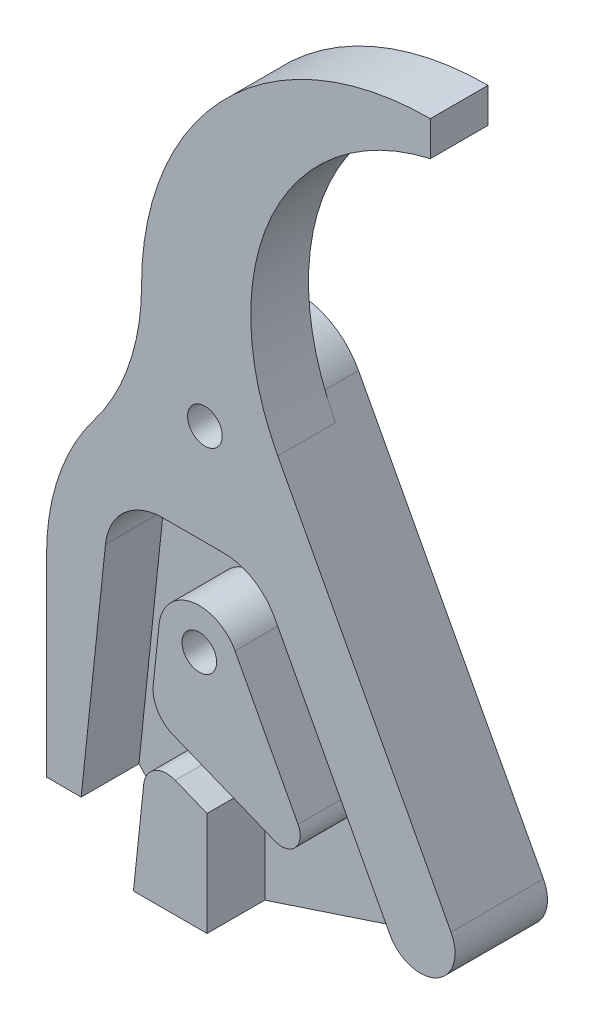
SolidWorks part; units mm, degrees
ref_plane "Alzado" through (0, 0, 0) normal (0, 0, 1) x (1, 0, 0)
ref_plane "Planta" through (0, 0, 0) normal (0, 1, 0) x (1, 0, 0)
ref_plane "Vista lateral" through (0, 0, 0) normal (1, 0, 0) x (0, 0, -1)
sketch "Croquis1" plane through (0, 0, 0) normal (0, 0, 1) x (1, 0, 0)
  line L0 (0, 0) -> (3.2081, 30.5226)
  line L1 (8.1807, 35) -> (13.4351, 35)
  line L2 (17.8498, 32.3474) -> (74.7762, -74.7155)
  line L3 (-45.5316, -5.3258) -> (-45.5316, 25.382)
  line L4 (0, 0) -> (0, 124.083) construction
  line L5 (14.4224, 28.1432) -> (19.8837, 17.8719)
  line L6 (7.8513, 26.8658) -> (7.3413, 22.014)
  line L7 (17.8498, 32.3474) -> (5.7848, 55.0384) construction
  line L8 (5.7848, 55.0384) -> (3.2081, 30.5226) construction
  line L9 (17.8538, 15.6175) -> (9.0466, 19.1759)
  line L10 (25.2121, 15.5) -> (11.8352, 15.5) construction
  line L11 (12.9137, 30) -> (5.536, 30) construction
  line L12 (6.4174, 22.7498) -> (9.4633, 17.0212) construction
  line L13 (5.0275, 0) -> (6.521, 14.2091)
  line L14 (9.2592, 15.8544) -> (17.7727, 12.4147)
  line L15 (6.3558, 16) -> (10.5824, 16) construction
  arc A0 (14.4224, 28.1432) -> (7.8513, 26.8658) centre (11.3321, 26.5) ccw
  arc A1 (17.8498, 32.3474) -> (13.4351, 35) centre (13.4351, 30) ccw
  arc A2 (8.1807, 35) -> (3.2081, 30.5226) centre (8.1807, 30) ccw
  arc A3 (7.3413, 22.014) -> (9.0466, 19.1759) centre (10.0771, 21.7264) ccw
  arc A4 (19.8837, 17.8719) -> (17.8538, 15.6175) centre (18.4585, 17.1142) cw
  arc A5 (6.521, 14.2091) -> (9.2592, 15.8544) centre (8.51, 14) cw
  dimension "D2" = 3.5
  dimension "D3" = 5
  dimension "D6" = 5
  dimension "D9" = 35
  dimension "D8" = 5
  dimension "D16" = 2
  dimension "D1" = 34
  dimension "D4" = 6
  dimension "D5" = 5
  dimension "D7" = 8.5
  dimension "D10" = 106
  dimension "D11" = 14.5
  dimension "D12" = 9.6
  dimension "D13" = 3
  dimension "D14" = 16
  dimension "D15" = 5
sketch "Croquis4" plane through (0, 0, 0) normal (0, 0, 1) x (1, 0, 0)
  line L0 (8.1807, 35) -> (13.4351, 35) construction
  line L1 (31.3321, 76.5) -> (69.3272, 76.5) construction
  line L2 (31.3321, 76.5) -> (31.3321, 73.5)
  line L3 (17.8538, 15.6175) -> (9.0466, 19.1759) construction
  line L5 (8.1807, 35) -> (13.4351, 35)
  line L6 (7.8513, 26.8658) -> (7.3413, 22.014)
  line L7 (7.8513, 26.8658) -> (7.3413, 22.014) construction
  line L8 (3.2081, 30.5226) -> (1.106, 10.5226)
  line L9 (0, 0) -> (3.2081, 30.5226) construction
  line L10 (17.8498, 32.3474) -> (27.8225, 13.5916)
  line L11 (17.8498, 32.3474) -> (74.7762, -74.7155) construction
  line L12 (6.521, 14.2091) -> (5.6316, 5.747)
  line L13 (14.4224, 28.1432) -> (19.8837, 17.8719) construction
  line L14 (17.8538, 15.6175) -> (9.0466, 19.1759)
  line L15 (1.106, 10.5226) -> (-1.894, 10.5226)
  line L16 (-1.894, 10.5226) -> (-1.894, 27.2014)
  line L17 (14.4224, 28.1432) -> (19.8837, 17.8719)
  line L18 (33.1201, 16.4084) -> (18.124, 44.6121)
  line L19 (5.0275, 0) -> (6.521, 14.2091) construction
  line L20 (9.2592, 15.8544) -> (12, 14.747)
  line L21 (9.2592, 15.8544) -> (17.7727, 12.4147) construction
  line L22 (12, 14.747) -> (12, 5.747)
  line L23 (12, 5.747) -> (5.6316, 5.747)
  line L25 (0, 0) -> (0, 124.083) construction
  line L26 (6.3321, 51.5) -> (-1.894, 27.2014) construction
  line L27 (17.8498, 32.3474) -> (5.7848, 55.0384) construction
  arc A0 (17.8498, 32.3474) -> (13.4351, 35) centre (13.4351, 30) ccw construction
  arc A1 (8.1807, 35) -> (3.2081, 30.5226) centre (8.1807, 30) ccw construction
  arc A2 (14.4224, 28.1432) -> (7.8513, 26.8658) centre (11.3321, 26.5) ccw construction
  arc A3 (17.8498, 32.3474) -> (13.4351, 35) centre (13.4351, 30) ccw
  arc A4 (8.1807, 35) -> (3.2081, 30.5226) centre (8.1807, 30) ccw
  arc A5 (14.4224, 28.1432) -> (7.8513, 26.8658) centre (11.3321, 26.5) ccw
  circle A6 centre (11.3321, 26.5) radius 1.5
  arc A7 (27.8225, 13.5916) -> (33.1201, 16.4084) centre (30.4713, 15) ccw
  arc A8 (7.3413, 22.014) -> (9.0466, 19.1759) centre (10.0771, 21.7264) ccw construction
  arc A9 (31.3321, 76.5) -> (6.3321, 51.5) centre (31.3321, 51.5) ccw
  arc A10 (31.3321, 73.5) -> (18.124, 44.6121) centre (35.7829, 54.0015) ccw
  arc A11 (17.8538, 15.6175) -> (19.8837, 17.8719) centre (18.4585, 17.1142) ccw construction
  arc A12 (7.3413, 22.014) -> (9.0466, 19.1759) centre (10.0771, 21.7264) ccw
  arc A13 (17.8538, 15.6175) -> (19.8837, 17.8719) centre (18.4585, 17.1142) ccw
  arc A14 (6.521, 14.2091) -> (9.2592, 15.8544) centre (8.51, 14) cw
  arc A15 (6.3321, 51.5) -> (2.219, 39.3507) centre (-13.6679, 51.5) cw
  arc A16 (2.219, 39.3507) -> (-1.894, 27.2014) centre (18.106, 27.2014) ccw
  circle A17 centre (11.8173, 43.6929) radius 1.5
  dimension "D1" = 3
  dimension "D9" = 3
  dimension "D6" = 20
  dimension "D12" = 20
  dimension "D13" = 20
  dimension "D14" = 25
  dimension "D15" = 3
  dimension "D2" = 20
  dimension "D3" = 3
  dimension "D4" = 20
  dimension "D5" = 3
  dimension "D7" = 50
  dimension "D8" = 20
  dimension "D10" = 12
  dimension "D11" = 9
extrude "Saliente-Extruir1" add sketch "Croquis4" along normal blind 5
sketch "Croquis5" plane through (0, 0, 0) normal (0, 0, 1) x (1, 0, 0)
  line L3 (-1.894, 10.5226) -> (-1.894, 27.2014) construction
  line L4 (1.106, 10.5226) -> (-1.894, 10.5226) construction
  line L8 (33.1201, 16.4084) -> (18.124, 44.6121) construction
  line L13 (12, 5.747) -> (5.6316, 5.747) construction
  line L14 (12, 5.747) -> (31.4112, 12.151)
  line L15 (1.106, 10.5226) -> (5.6316, 5.747)
  line L16 (3.6956, 41.5749) -> (6.6082, 46.6704)
  line L17 (-1.894, 10.5226) -> (-1.894, 27.2014)
  line L18 (1.106, 10.5226) -> (-1.894, 10.5226)
  line L22 (33.1201, 16.4084) -> (17.115, 46.5097)
  line L27 (12, 5.747) -> (5.6316, 5.747)
  arc A0 (2.219, 39.3507) -> (3.6956, 41.5749) centre (-13.6679, 51.5) ccw
  circle A4 centre (11.8173, 43.6929) radius 1.5 construction
  arc A6 (2.219, 39.3507) -> (-1.894, 27.2014) centre (18.106, 27.2014) ccw construction
  arc A13 (33.1201, 16.4084) -> (31.4112, 12.151) centre (30.4713, 15) cw
  circle A14 centre (11.3321, 26.5) radius 1.5 construction
  circle A15 centre (11.3321, 26.5) radius 1.5
  arc A16 (17.115, 46.5097) -> (6.6082, 46.6704) centre (11.8173, 43.6929) ccw
  circle A17 centre (11.8173, 43.6929) radius 1.5
  arc A19 (2.219, 39.3507) -> (-1.894, 27.2014) centre (18.106, 27.2014) ccw
  arc A20 (2.219, 39.3507) -> (6.3321, 51.5) centre (-13.6679, 51.5) ccw construction
extrude "Saliente-Extruir2" add sketch "Croquis5" against normal blind 3
